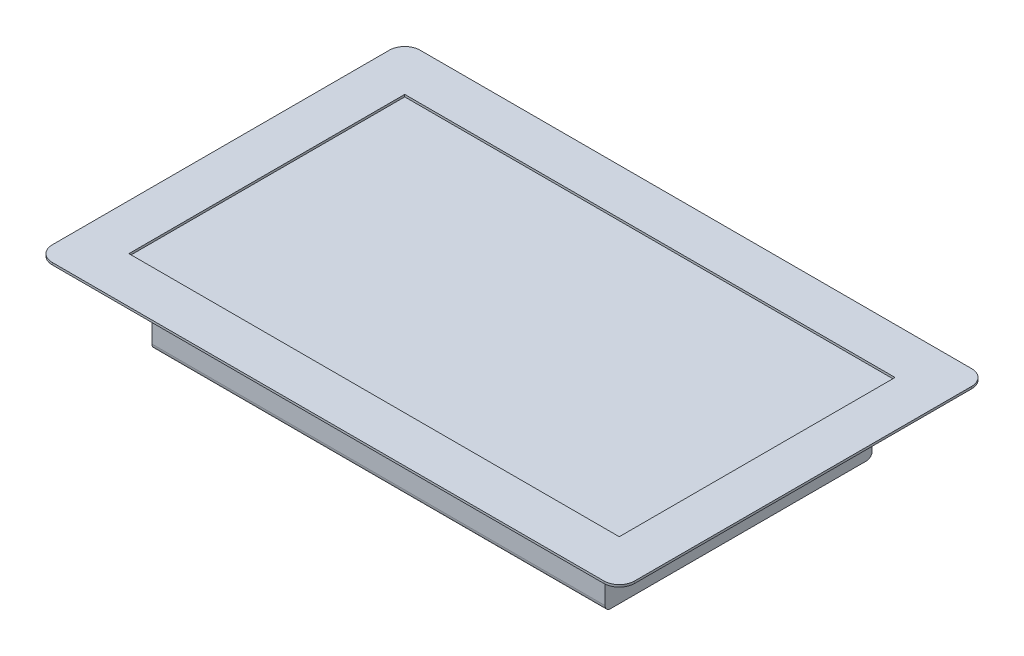
SolidWorks part; units mm, degrees
ref_plane "Front Plane" through (0, 0, 0) normal (0, 0, 1) x (1, 0, 0)
ref_plane "Top Plane" through (0, 0, 0) normal (0, 1, 0) x (1, 0, 0)
ref_plane "Right Plane" through (0, 0, 0) normal (1, 0, 0) x (0, 0, -1)
sketch "Sketch1" plane through (0, 0, 0) normal (0, 1, 0) x (1, 0, 0)
  line L1 (133, -84) -> (-133, -84)
  line L2 (133, -84) -> (133, 84)
  line L3 (133, 84) -> (-133, 84)
  line L4 (-133, -84) -> (-133, 84)
  line L5 (133, -84) -> (-133, 84) construction
  line L6 (133, 84) -> (-133, -84) construction
  point P0 (0, 0)
  dimension "D1" = 168
  dimension "D2" = 266
extrude "Boss-Extrude1" add sketch "Sketch1" along normal blind 1
sketch "Sketch2" plane through (0, 0, 0) normal (0, 1, 0) x (1, 0, 0)
  line L1 (123.5, 74.5) -> (-123.5, 74.5)
  line L2 (123.5, 74.5) -> (123.5, -74.5)
  line L3 (123.5, -74.5) -> (-123.5, -74.5)
  line L4 (-123.5, 74.5) -> (-123.5, -74.5)
  line L5 (123.5, 74.5) -> (-123.5, -74.5) construction
  line L6 (123.5, -74.5) -> (-123.5, 74.5) construction
  point P0 (0, 0)
  dimension "D1" = 247
  dimension "D2" = 149
extrude "Boss-Extrude2" add sketch "Sketch2" against normal blind 7
sketch "Sketch3" plane through (0, 0, 0) normal (1, 0, 0) x (0, 0, -1)
  line L0 (-73, -7) -> (73, -7)
  line L1 (-74.5, -7) -> (74.5, -7) construction
  line L2 (73, -7) -> (73, -8)
  line L3 (73, -8) -> (61, -8)
  line L4 (61, -8) -> (61, -34)
  line L5 (61, -34) -> (-61, -34)
  line L6 (-61, -34) -> (-61, -8)
  line L7 (-61, -8) -> (-73, -8)
  line L8 (-73, -8) -> (-73, -7)
  line L9 (-74.5, -7) -> (-74.5, 0) construction
  line L10 (0, 0) -> (0, -7) construction
  line L11 (0, -7) -> (0, -34) construction
  dimension "D1" = 1
  dimension "D2" = 1.5
  dimension "D3" = 122
  dimension "D4" = 27
extrude "Boss-Extrude3" add sketch "Sketch3" along normal mid plane 207
fillet "Fillet1" radius 7 4 edges at (133, 0.5, -84) (-133, 0.5, -84) (-133, 0.5, 84) (133, 0.5, 84)
fillet "Fillet2" radius 1 4 edges at (-123.5, -3.5, 74.5) (-123.5, -3.5, -74.5) (123.5, -3.5, 74.5) (123.5, -3.5, -74.5)
fillet "Fillet3" radius 2.5 6 edges at (-103.5, -7.5, 73) (103.5, -7.5, 73) (103.5, -7.5, -73) (-103.5, -7.5, -73) (0, -34, -61) (0, -34, 61)
sketch "Sketch4" plane through (0, 1, 0) normal (0, 1, 0) x (1, 0, 0)
  line L1 (112, -63) -> (-112, -63)
  line L2 (112, -63) -> (112, 63)
  line L3 (112, 63) -> (-112, 63)
  line L4 (-112, -63) -> (-112, 63)
  line L5 (112, -63) -> (-112, 63) construction
  line L6 (112, 63) -> (-112, -63) construction
  point P0 (0, 0)
  dimension "D1" = 224
  dimension "D2" = 126
extrude "Cut-Extrude1" cut sketch "Sketch4" against normal blind 1
